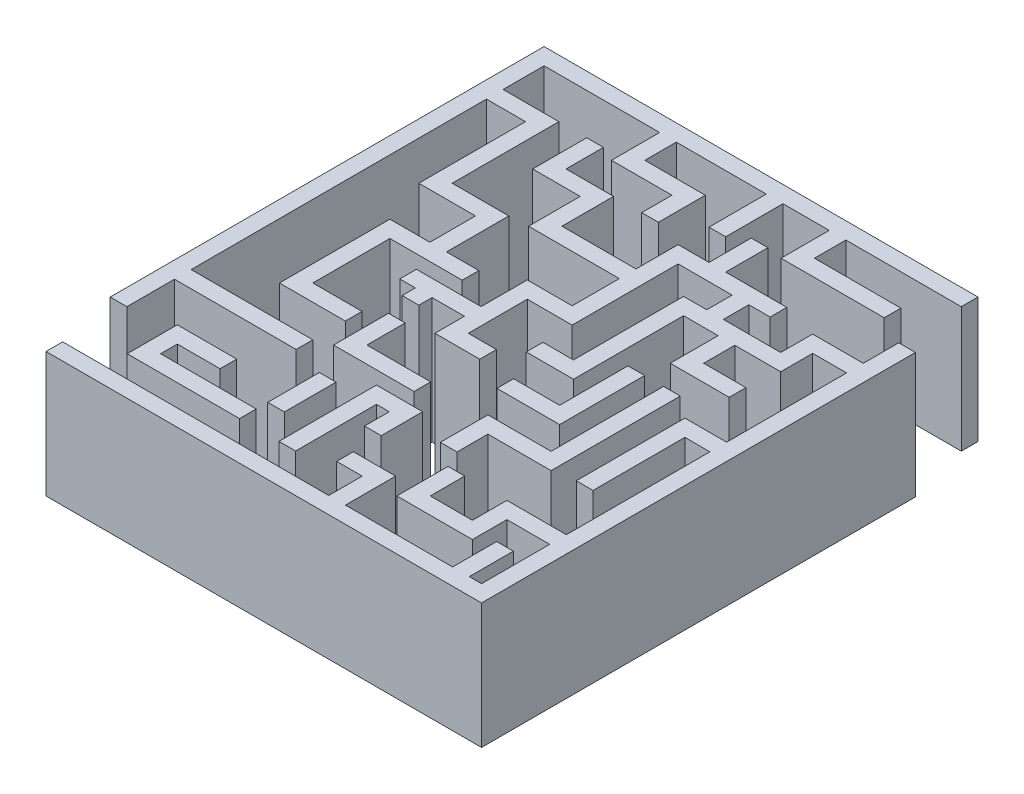
SolidWorks part; units mm, degrees
ref_plane "Front Plane" through (0, 0, 0) normal (0, 0, 1) x (1, 0, 0)
ref_plane "Top Plane" through (0, 0, 0) normal (0, 1, 0) x (1, 0, 0)
ref_plane "Right Plane" through (0, 0, 0) normal (1, 0, 0) x (0, 0, -1)
sketch "Sketch1" plane through (0, 0, 0) normal (0, 1, 0) x (1, 0, 0)
  line L0 (-2480.3622, 2812.7352) -> (-2480.3622, 2321.6456)
  line L1 (-2480.3622, 2812.7352) -> (-1096.0115, 2812.7352)
  line L2 (-2499.9782, -2937.0083) -> (688.5158, -2937.0083)
  line L3 (2519.6378, -2937.0083) -> (2519.6378, -2120.3234)
  line L4 (-2480.3622, 2321.6456) -> (-1812.2422, 2321.6456)
  line L5 (-1812.2422, 2321.6456) -> (-1812.2422, 1043.3555)
  line L6 (-1812.2422, 1043.3555) -> (-1133.5646, 1043.3555)
  line L7 (-1133.5646, 1043.3555) -> (-1133.5646, 296.7893)
  line L8 (-1812.2422, 296.7893) -> (-1333.5646, 296.7893)
  line L9 (-1812.2422, 296.7893) -> (-1812.2422, -1027.1883)
  line L10 (-1812.2422, -1027.1883) -> (-1022.3059, -1027.1883)
  line L11 (-2480.3622, -1616.8591) -> (-1022.3059, -1616.8591)
  line L12 (-1278.2008, -2073.0194) -> (-1990.256, -2073.0194)
  line L13 (-1990.256, -2073.0194) -> (-1990.256, -2673.816)
  line L14 (-1990.256, -2673.816) -> (-644.0266, -2673.816)
  line L15 (-2680.3622, 3012.7352) -> (2519.6378, 3012.7352)
  line L16 (-1278.2008, 2321.6456) -> (-1278.2008, 1873.837)
  line L17 (-1278.2008, 1873.837) -> (-708.7461, 1873.837)
  line L18 (-708.7461, 1873.837) -> (-708.7461, 1255.0469)
  line L19 (-708.7461, 1255.0469) -> (178.7292, 1255.0469)
  line L20 (-896.0115, 2812.7352) -> (-896.0115, 2435.6333)
  line L21 (-896.0115, 2435.6333) -> (-171.3757, 2435.6333)
  line L22 (-171.3757, 2435.6333) -> (-171.3757, 1873.837)
  line L23 (382.2786, 2812.7352) -> (382.2786, 2126.2382)
  line L24 (1136.3504, 2812.7352) -> (1136.3504, 2435.6333)
  line L25 (1136.3504, 2435.6333) -> (2172.7493, 2435.6333)
  line L26 (-644.0266, -1716.774) -> (-644.0266, -2335.5642)
  line L27 (-171.3757, -2673.816) -> (-171.3757, -1505.0827)
  line L28 (-171.3757, -1505.0827) -> (382.2786, -1505.0827)
  line L29 (382.2786, -1505.0827) -> (382.2786, -2001.7432)
  line L30 (382.2786, -2335.5642) -> (888.5158, -2335.5642)
  line L31 (888.5158, -2335.5642) -> (888.5158, -2937.0083)
  line L32 (2172.7493, -2408.8419) -> (2172.7493, -2937.0083)
  line L33 (2519.6378, -1920.3234) -> (1807.1242, -1920.3234)
  line L34 (1807.1242, -1920.3234) -> (1807.1242, -2333.953)
  line L35 (1807.1242, -2333.953) -> (1301.5734, -2333.953)
  line L36 (1301.5734, -2333.953) -> (1301.5734, -1920.3234)
  line L37 (2519.6378, 0) -> (2019.6282, 0)
  line L38 (2019.6282, 0) -> (2019.6282, -1301.5333)
  line L39 (1562.9167, 200.9665) -> (1562.9167, -1146.8358)
  line L40 (1562.9167, -1146.8358) -> (805.6613, -1146.8358)
  line L41 (805.6613, -1146.8358) -> (805.6613, -1716.774)
  line L42 (2519.6378, 1637.7197) -> (1912.9699, 1637.7197)
  line L43 (1912.9699, 1637.7197) -> (1912.9699, 1255.0469)
  line L44 (1912.9699, 1255.0469) -> (1226.1109, 1255.0469)
  line L45 (748.6675, 1255.0469) -> (748.6675, -63.9531)
  line L46 (748.6675, -63.9531) -> (382.2786, -63.9531)
  line L47 (1481.4452, 1759.8494) -> (748.6675, 1759.8494)
  line L48 (178.7292, 1759.8494) -> (178.7292, 1255.0469)
  line L49 (178.7292, 489.7012) -> (-358.6412, 489.7012)
  line L50 (-358.6412, 489.7012) -> (-358.6412, -63.9531)
  line L51 (-358.6412, -617.6074) -> (178.7292, -617.6074)
  line L52 (-358.6412, -63.9531) -> (-1133.5646, -63.9531)
  line L53 (-746.1029, -263.9531) -> (-746.1029, -422.2)
  line L54 (748.6675, 1759.8494) -> (748.6675, 2266.1647)
  line L55 (1226.1109, 1559.8494) -> (1226.1109, 1255.0469)
  line L56 (1562.9167, 1055.0469) -> (1562.9167, 681.7155)
  line L57 (1562.9167, 681.7155) -> (2068.752, 681.7155)
  line L58 (1136.3504, 200.9665) -> (1136.3504, -617.6074)
  line L59 (1136.3504, -617.6074) -> (584.5864, -617.6074)
  line L60 (-644.0266, -688.4191) -> (-644.0266, -1146.8358)
  line L61 (-644.0266, -1146.8358) -> (120.6697, -1146.8358)
  line L62 (-2680.3622, 3012.7352) -> (-2680.3622, -2187.2648)
  line L63 (-2499.9782, -3137.0083) -> (2719.6378, -3137.0083)
  line L64 (2719.6378, -3137.0083) -> (2719.6378, 2062.7352)
  line L65 (-2480.3622, 2121.6456) -> (-2012.2422, 2121.6456)
  line L66 (-2012.2422, 2121.6456) -> (-2012.2422, 843.3555)
  line L67 (-2012.2422, 843.3555) -> (-1333.5646, 843.3555)
  line L68 (-1333.5646, 843.3555) -> (-1333.5646, 296.7893)
  line L69 (-1612.2422, -827.1883) -> (-1022.3059, -827.1883)
  line L70 (-1612.2422, 96.7893) -> (-1612.2422, -827.1883)
  line L71 (-1612.2422, 96.7893) -> (-746.1029, 96.7893)
  line L72 (-746.1029, 296.7893) -> (-746.1029, 96.7893)
  line L73 (-1022.3059, -827.1883) -> (-1022.3059, -1027.1883)
  line L74 (-1133.5646, 296.7893) -> (-746.1029, 296.7893)
  line L75 (-2680.3622, -2187.2648) -> (-2480.3622, -2187.2648)
  line L76 (-1812.2422, 296.7893) -> (-746.1029, 296.7893) construction
  line L77 (2519.6378, 3012.7352) -> (2519.6378, 2812.7352)
  line L78 (2519.6378, 2062.7352) -> (2719.6378, 2062.7352)
  line L79 (-2499.9782, -2937.0083) -> (-2499.9782, -3137.0083)
  line L80 (-1278.2008, -2273.0194) -> (-1790.256, -2273.0194)
  line L81 (-1790.256, -2273.0194) -> (-1790.256, -2473.816)
  line L82 (-1790.256, -2473.816) -> (-644.0266, -2473.816)
  line L83 (-1278.2008, -2273.0194) -> (-1278.2008, -2073.0194)
  line L84 (-644.0266, -2473.816) -> (-644.0266, -2673.816)
  line L85 (-444.0266, -1716.774) -> (-444.0266, -2335.5642)
  line L86 (-644.0266, -2335.5642) -> (-444.0266, -2335.5642)
  line L87 (-444.0266, -1716.774) -> (-644.0266, -1716.774)
  line L88 (-2480.3622, -1416.8591) -> (-1022.3059, -1416.8591)
  line L89 (-1022.3059, -1416.8591) -> (-1022.3059, -1616.8591)
  line L90 (-2480.3622, -1616.8591) -> (-2480.3622, -2187.2648)
  line L91 (-2480.3622, 2121.6456) -> (-2480.3622, -1416.8591)
  line L92 (-2480.3622, 2812.7352) -> (-2480.3622, -2187.2648) construction
  line L93 (1481.4452, 1559.8494) -> (1226.1109, 1559.8494)
  line L94 (378.7292, 1559.8494) -> (378.7292, 289.7012)
  line L95 (378.7292, 289.7012) -> (-158.6412, 289.7012)
  line L96 (-158.6412, 289.7012) -> (-158.6412, -417.6074)
  line L97 (-158.6412, -417.6074) -> (178.7292, -417.6074)
  line L98 (1481.4452, 1759.8494) -> (1481.4452, 1559.8494)
  line L99 (178.7292, -417.6074) -> (178.7292, -617.6074)
  line L100 (1026.1109, 1559.8494) -> (1026.1109, 1255.0469)
  line L101 (1026.1109, 1559.8494) -> (378.7292, 1559.8494)
  line L102 (1226.1109, 1759.8494) -> (1226.1109, 1255.0469) construction
  line L103 (1026.1109, 1759.8494) -> (1026.1109, 1255.0469) construction
  line L104 (2519.6378, 1437.7197) -> (2112.9699, 1437.7197)
  line L105 (1481.4452, 1559.8494) -> (378.7292, 1559.8494) construction
  line L106 (2112.9699, 1437.7197) -> (2112.9699, 1055.0469)
  line L107 (2112.9699, 1055.0469) -> (1562.9167, 1055.0469)
  line L108 (948.6675, 1055.0469) -> (948.6675, -263.9531)
  line L109 (948.6675, -263.9531) -> (382.2786, -263.9531)
  line L110 (1362.9167, 1055.0469) -> (1362.9167, 481.7155)
  line L111 (1362.9167, 481.7155) -> (2068.752, 481.7155)
  line L112 (2068.752, 681.7155) -> (2068.752, 481.7155)
  line L113 (382.2786, -63.9531) -> (382.2786, -263.9531)
  line L114 (1026.1109, 1255.0469) -> (748.6675, 1255.0469)
  line L115 (1362.9167, 1055.0469) -> (948.6675, 1055.0469)
  line L116 (1912.9699, 1255.0469) -> (748.6675, 1255.0469) construction
  line L117 (1362.9167, 1255.0469) -> (1362.9167, 481.7155) construction
  line L118 (1562.9167, 1255.0469) -> (1562.9167, 681.7155) construction
  line L119 (2519.6378, 1637.7197) -> (2519.6378, 2062.7352)
  line L120 (2112.9699, 1055.0469) -> (948.6675, 1055.0469) construction
  line L121 (1336.3504, 200.9665) -> (1336.3504, -817.6074)
  line L122 (2519.6378, -2937.0083) -> (2519.6378, 2062.7352) construction
  line L123 (1336.3504, -817.6074) -> (584.5864, -817.6074)
  line L124 (1762.9167, 200.9665) -> (1762.9167, -1346.8358)
  line L125 (1762.9167, -1346.8358) -> (1005.6613, -1346.8358)
  line L126 (1005.6613, -1346.8358) -> (1005.6613, -1716.774)
  line L127 (2519.6378, -200) -> (2219.6282, -200)
  line L128 (2219.6282, -200) -> (2219.6282, -1301.5333)
  line L129 (2019.6282, -1301.5333) -> (2219.6282, -1301.5333)
  line L130 (1136.3504, 200.9665) -> (1336.3504, 200.9665)
  line L131 (584.5864, -617.6074) -> (584.5864, -817.6074)
  line L132 (805.6613, -1716.774) -> (1005.6613, -1716.774)
  line L133 (1562.9167, 200.9665) -> (1762.9167, 200.9665)
  line L134 (2519.6378, 0) -> (2519.6378, 1437.7197)
  line L135 (382.2786, -2535.5642) -> (688.5158, -2535.5642)
  line L136 (688.5158, -2535.5642) -> (688.5158, -2937.0083)
  line L137 (2519.6378, -2120.3234) -> (2007.1242, -2120.3234)
  line L138 (2007.1242, -2120.3234) -> (2007.1242, -2533.953)
  line L139 (2007.1242, -2533.953) -> (1101.5734, -2533.953)
  line L140 (1101.5734, -2533.953) -> (1101.5734, -1920.3234)
  line L141 (2372.7493, -2408.8419) -> (2372.7493, -2937.0083)
  line L142 (1101.5734, -1920.3234) -> (1301.5734, -1920.3234)
  line L143 (382.2786, -2335.5642) -> (382.2786, -2535.5642)
  line L144 (2172.7493, -2408.8419) -> (2372.7493, -2408.8419)
  line L145 (2372.7493, -2937.0083) -> (2519.6378, -2937.0083)
  line L146 (888.5158, -2937.0083) -> (2172.7493, -2937.0083)
  line L147 (-2499.9782, -2937.0083) -> (2519.6378, -2937.0083) construction
  line L148 (2519.6378, -1920.3234) -> (2519.6378, -200)
  line L149 (-844.0266, -688.4191) -> (-844.0266, -1346.8358)
  line L150 (-844.0266, -1346.8358) -> (120.6697, -1346.8358)
  line L151 (28.6243, -2673.816) -> (28.6243, -1705.0827)
  line L152 (28.6243, -1705.0827) -> (182.2786, -1705.0827)
  line L153 (182.2786, -1705.0827) -> (182.2786, -2001.7432)
  line L154 (-844.0266, -688.4191) -> (-644.0266, -688.4191)
  line L155 (120.6697, -1146.8358) -> (120.6697, -1346.8358)
  line L156 (182.2786, -2001.7432) -> (382.2786, -2001.7432)
  line L157 (-171.3757, -2673.816) -> (28.6243, -2673.816)
  line L158 (-1478.2008, 2321.6456) -> (-1478.2008, 1673.837)
  line L159 (-1478.2008, 1673.837) -> (-908.7461, 1673.837)
  line L160 (-908.7461, 1673.837) -> (-908.7461, 1055.0469)
  line L161 (-908.7461, 1055.0469) -> (178.7292, 1055.0469)
  line L162 (-1096.0115, 2812.7352) -> (-1096.0115, 2235.6333)
  line L163 (-1096.0115, 2235.6333) -> (-371.3757, 2235.6333)
  line L164 (-371.3757, 2235.6333) -> (-371.3757, 1873.837)
  line L165 (936.3504, 2812.7352) -> (936.3504, 2235.6333)
  line L166 (936.3504, 2235.6333) -> (2172.7493, 2235.6333)
  line L167 (182.2786, 2812.7352) -> (182.2786, 2126.2382)
  line L168 (548.6675, 1759.8494) -> (548.6675, 2266.1647)
  line L169 (-358.6412, -263.9531) -> (-746.1029, -263.9531)
  line L170 (-946.1029, -263.9531) -> (-946.1029, -422.2)
  line L171 (-1133.5646, -63.9531) -> (-1133.5646, -263.9531)
  line L172 (-946.1029, -422.2) -> (-746.1029, -422.2)
  line L173 (2172.7493, 2435.6333) -> (2172.7493, 2235.6333)
  line L174 (182.2786, 2126.2382) -> (382.2786, 2126.2382)
  line L175 (548.6675, 2266.1647) -> (748.6675, 2266.1647)
  line L176 (-371.3757, 1873.837) -> (-171.3757, 1873.837)
  line L177 (-1478.2008, 2321.6456) -> (-1278.2008, 2321.6456)
  line L178 (-946.1029, -263.9531) -> (-1133.5646, -263.9531)
  line L179 (-946.1029, -63.9531) -> (-946.1029, -422.2) construction
  line L180 (-746.1029, -63.9531) -> (-746.1029, -422.2) construction
  line L181 (-358.6412, -263.9531) -> (-358.6412, -617.6074)
  line L182 (-358.6412, -263.9531) -> (-1133.5646, -263.9531) construction
  line L183 (178.7292, 1055.0469) -> (178.7292, 489.7012)
  line L184 (-358.6412, 489.7012) -> (-358.6412, -617.6074) construction
  line L185 (548.6675, 1759.8494) -> (178.7292, 1759.8494)
  line L186 (178.7292, 1759.8494) -> (178.7292, 489.7012) construction
  line L187 (1136.3504, 2812.7352) -> (2519.6378, 2812.7352)
  line L188 (1481.4452, 1759.8494) -> (178.7292, 1759.8494) construction
  line L189 (382.2786, 2812.7352) -> (936.3504, 2812.7352)
  line L190 (-2480.3622, 2812.7352) -> (2519.6378, 2812.7352) construction
  line L191 (-896.0115, 2812.7352) -> (182.2786, 2812.7352)
  point P3 (-2480.3622, 312.7352)
  dimension "D1" = 5000
  dimension "D2" = 2500
  dimension "D3" = 5000
  dimension "D4" = 750
  dimension "D5" = 750
  dimension "D6" = 200
  dimension "D7" = 200
  dimension "D8" = 200
  dimension "D9" = 200
  dimension "D10" = 200
  dimension "D11" = 200
  dimension "D12" = 200
  dimension "D13" = 200
  dimension "D14" = 200
  dimension "D15" = 200
  dimension "D16" = 200
  dimension "D17" = 200
  dimension "D18" = 200
  dimension "D19" = 200
  dimension "D20" = 200
  dimension "D21" = 200
  dimension "D22" = 200
  dimension "D23" = 200
  dimension "D24" = 200
  dimension "D25" = 200
  dimension "D26" = 200
  dimension "D27" = 200
  dimension "D28" = 200
  dimension "D29" = 200
  dimension "D30" = 200
extrude "Boss-Extrude1" add sketch "Sketch1" along normal blind 1500
